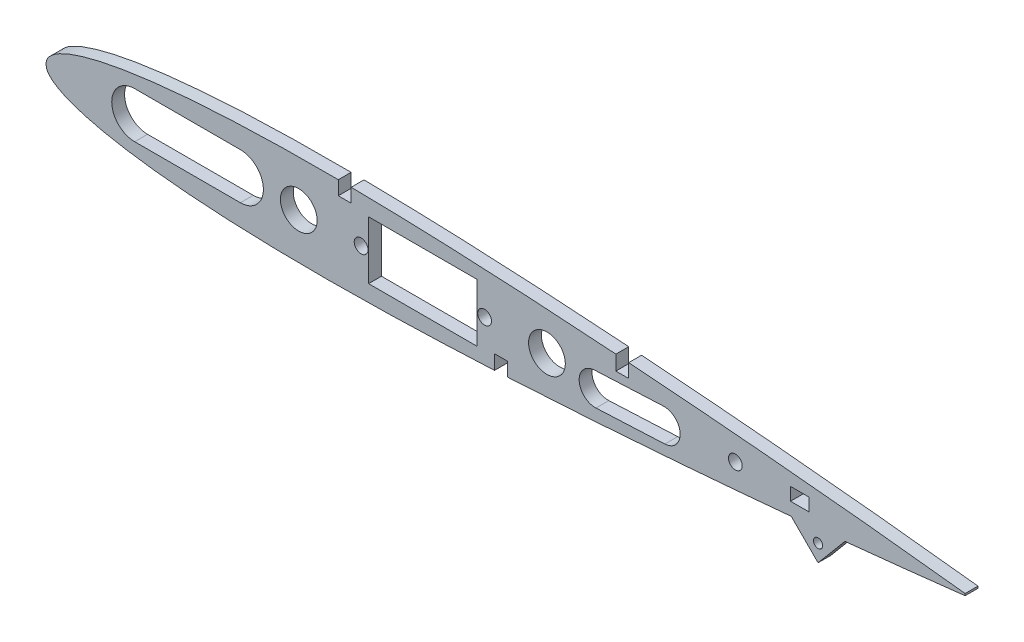
SolidWorks part; units mm, degrees
material "Фанера"
ref_plane "Спереди" through (0, 0, 0) normal (0, 0, 1) x (1, 0, 0)
ref_plane "Сверху" through (0, 0, 0) normal (0, 1, 0) x (1, 0, 0)
ref_plane "Справа" through (0, 0, 0) normal (1, 0, 0) x (0, 0, -1)
curve "Кривая1"
  spline degree 3 poles (200, 0.21, 0) (199.5201, 0.266, 0) (198.1795, 0.4223, 0) (195.7476, 0.7017, 0) (192.5308, 1.0651, 0) (188.7716, 1.4807, 0) (184.587, 1.9325, 0) (180.0562, 2.4092, 0) (175.2384, 2.9026, 0) (170.1814, 3.4057, 0) (164.925, 3.9132, 0) (159.5032, 4.4204, 0) (153.9461, 4.9234, 0) (148.2803, 5.4186, 0) (142.5299, 5.9028, 0) (136.7168, 6.3729, 0) (130.8615, 6.8262, 0) (124.9826, 7.2598, 0) (119.0976, 7.6711, 0) (113.2231, 8.0575, 0) (107.3746, 8.4163, 0) (101.5666, 8.7448, 0) (95.8133, 9.0407, 0) (90.1279, 9.3014, 0) (84.5231, 9.5247, 0) (79.0111, 9.7082, 0) (73.6037, 9.85, 0) (68.3121, 9.9482, 0) (63.1472, 10.0012, 0) (58.1196, 10.0077, 0) (53.2393, 9.9665, 0) (48.5164, 9.8771, 0) (43.9603, 9.7388, 0) (39.5803, 9.5517, 0) (35.3856, 9.3161, 0) (31.3849, 9.0325, 0) (27.5868, 8.7017, 0) (23.9997, 8.3252, 0) (20.6317, 7.9043, 0) (17.4909, 7.4408, 0) (14.5849, 6.9366, 0) (11.9213, 6.3939, 0) (9.5074, 5.8148, 0) (7.3502, 5.2016, 0) (5.4564, 4.5565, 0) (3.8315, 3.8815, 0) (2.4822, 3.178, 0) (1.4075, 2.4454, 0) (0.6238, 1.6789, 0) (0.1006, 0.8638, 0) (0.0324, 0.2785, 0) (0, 0, 0) knots 0 0 0 0 0.007145 0.019956 0.036196 0.055011 0.075879 0.098429 0.122376 0.147488 0.173572 0.20046 0.228005 0.256076 0.284555 0.313333 0.34231 0.371393 0.400496 0.429538 0.458442 0.487136 0.515552 0.543624 0.57129 0.598491 0.62517 0.651272 0.676746 0.701542 0.725611 0.748908 0.771388 0.793008 0.813728 0.833508 0.85231 0.870097 0.886836 0.902493 0.917037 0.930441 0.94268 0.953734 0.96359 0.972247 0.979722 0.986065 0.991385 0.995901 1 1 1 1
curve "Кривая2"
  spline degree 3 poles (0, 0, 0) (0.0324, -0.2785, 0) (0.1006, -0.8638, 0) (0.6238, -1.6789, 0) (1.4075, -2.4454, 0) (2.4822, -3.178, 0) (3.8315, -3.8815, 0) (5.4564, -4.5565, 0) (7.3502, -5.2016, 0) (9.5074, -5.8148, 0) (11.9213, -6.3939, 0) (14.5849, -6.9366, 0) (17.4909, -7.4408, 0) (20.6317, -7.9043, 0) (23.9997, -8.3252, 0) (27.5868, -8.7017, 0) (31.3849, -9.0325, 0) (35.3856, -9.3161, 0) (39.5803, -9.5517, 0) (43.9603, -9.7388, 0) (48.5164, -9.8771, 0) (53.2393, -9.9665, 0) (58.1196, -10.0077, 0) (63.1472, -10.0012, 0) (68.3121, -9.9482, 0) (73.6037, -9.85, 0) (79.0111, -9.7082, 0) (84.5231, -9.5247, 0) (90.1279, -9.3014, 0) (95.8133, -9.0407, 0) (101.5666, -8.7448, 0) (107.3746, -8.4163, 0) (113.2231, -8.0575, 0) (119.0976, -7.6711, 0) (124.9826, -7.2598, 0) (130.8615, -6.8262, 0) (136.7168, -6.3729, 0) (142.5299, -5.9028, 0) (148.2803, -5.4186, 0) (153.9461, -4.9234, 0) (159.5032, -4.4204, 0) (164.925, -3.9132, 0) (170.1814, -3.4057, 0) (175.2384, -2.9026, 0) (180.0562, -2.4092, 0) (184.587, -1.9325, 0) (188.7716, -1.4807, 0) (192.5308, -1.0651, 0) (195.7476, -0.7017, 0) (198.1795, -0.4223, 0) (199.5201, -0.266, 0) (200, -0.21, 0) knots 0 0 0 0 0.004099 0.008615 0.013935 0.020278 0.027753 0.03641 0.046266 0.05732 0.069559 0.082963 0.097507 0.113164 0.129903 0.14769 0.166492 0.186272 0.206992 0.228612 0.251092 0.274389 0.298458 0.323254 0.348728 0.37483 0.401509 0.42871 0.456376 0.484448 0.512864 0.541558 0.570462 0.599504 0.628607 0.65769 0.686667 0.715445 0.743924 0.771995 0.79954 0.826428 0.852512 0.877624 0.901571 0.924121 0.944989 0.963804 0.980044 0.992855 1 1 1 1
sketch "Эскиз3" plane through (0, 0, 0) normal (0, 0, 1) x (1, 0, 0)
  line L0 (200, 0.21) -> (200, -0.21)
  line L1 (63.6, 9.9908) -> (63.6, 6.9656)
  line L2 (63.6, 6.9656) -> (66.4, 6.9656)
  line L3 (66.4, 6.9656) -> (66.4, 9.9656)
  line L4 (97.6, -8.9469) -> (97.6, -5.8023)
  line L5 (97.6, -5.8023) -> (100.4, -5.8023)
  line L6 (100.4, -5.8023) -> (100.4, -8.8023)
  line L7 (124, 7.3263) -> (124, 4.1244)
  line L8 (124, 4.1244) -> (126.8, 4.1244)
  line L9 (126.8, 4.1244) -> (126.8, 7.1244)
  line L10 (19.3, 0) -> (42.3, 0) construction
  line L11 (19.3, 5) -> (42.3, 5)
  line L12 (19.3, -5) -> (42.3, -5)
  line L13 (93.8, 6.3) -> (97.07, 6.3) construction
  line L16 (119.5083, -1.5033) -> (134.4917, -0.7967) construction
  line L17 (119.3435, 1.9928) -> (134.3268, 2.6994)
  line L18 (119.6732, -4.9994) -> (134.6565, -4.2928)
  line L19 (70.2, 6.3) -> (93.8, 6.3)
  line L20 (70.2, 6.3) -> (70.2, -6.3)
  line L21 (70.2, -6.3) -> (93.8, -6.3)
  line L22 (93.8, 6.3) -> (93.8, -6.3)
  line L23 (97.07, 6.3) -> (97.07, -6.3) construction
  line L24 (97.07, -6.3) -> (93.8, -6.3) construction
  line L25 (70.2, 6.3) -> (66.93, 6.3) construction
  line L26 (66.93, 6.3) -> (66.93, -6.3) construction
  line L27 (66.93, -6.3) -> (70.2, -6.3) construction
  line L28 (70.2, 6.3) -> (93.8, -6.3) construction
  line L29 (93.8, 6.3) -> (70.2, -6.3) construction
  line L30 (162.1702, -4.1702) -> (168, -10)
  line L31 (162, 1.4) -> (166, 1.4)
  line L32 (162, 1.4) -> (162, -1.4)
  line L33 (162, -1.4) -> (166, -1.4)
  line L34 (166, 1.4) -> (166, -1.4)
  line L35 (162, 1.4) -> (166, -1.4) construction
  line L36 (162, -1.4) -> (166, 1.4) construction
  line L37 (168, -10) -> (173.8395, -3.0408)
  line L38 (168, 8.0416) -> (168, -13.6699) construction
  circle A0 centre (109, 0) radius 4
  circle A1 centre (55, 0) radius 4
  arc A2 (150, 5.2672) -> (150, -5.2672) centre (150, 0) ccw
  arc A3 (142.8327, 5.8745) -> (142.8327, -5.8745) centre (150, 0) ccw
  circle A4 centre (150, 0) radius 1.5
  arc A5 (19.3, 5) -> (19.3, -5) centre (19.3, 0) ccw
  arc A6 (42.3, -5) -> (42.3, 5) centre (42.3, 0) ccw
  arc A9 (119.3435, 1.9928) -> (119.6732, -4.9994) centre (119.5083, -1.5033) ccw
  arc A10 (134.6565, -4.2928) -> (134.3268, 2.6994) centre (134.4917, -0.7967) ccw
  circle A11 centre (68.565, 0) radius 1.5
  circle A12 centre (95.435, 0) radius 1.5
  circle A13 centre (168, -6.3) radius 1
  spline S0 degree 3 poles (-9532.9695, -2992.5013) (170.2259, 85.6726) (-8.3379, 12.2838) (0.6238, -1.6789) (1.4075, -2.4454) (2.4822, -3.178) (3.8315, -3.8815) (5.4564, -4.5565) (7.3502, -5.2016) (9.5074, -5.8148) (11.9213, -6.3939) (14.5849, -6.9366) (17.4909, -7.4408) (20.6317, -7.9043) (23.9997, -8.3252) (27.5868, -8.7017) (31.3849, -9.0325) (35.3856, -9.3161) (39.5803, -9.5517) (43.9603, -9.7388) (48.5164, -9.8771) (53.2393, -9.9665) (58.1196, -10.0077) (63.1472, -10.0012) (68.3121, -9.9482) (73.6037, -9.85) (79.0111, -9.7082) (84.5231, -9.5247) (90.1279, -9.3014) (95.8133, -9.0407) (101.5666, -8.7448) (107.3746, -8.4163) (113.2231, -8.0575) (119.0976, -7.6711) (124.9826, -7.2598) (130.8615, -6.8262) (136.7168, -6.3729) (142.5299, -5.9028) (148.2803, -5.4186) (153.9461, -4.9234) (161.2601, -4.2614) (168.3719, -3.5857) (175.2384, -2.9026) (180.0562, -2.4092) (184.587, -1.9325) (188.7716, -1.4807) (192.5308, -1.0651) (195.7476, -0.7017) (353.0587, 17.3703) (505.6517, 66.5515) (1814.7464, -9851.1465) knots -0.224768 -0.224768 -0.224768 -0.224768 0.004099 0.008615 0.013935 0.020278 0.027753 0.03641 0.046266 0.05732 0.069559 0.082963 0.097507 0.113164 0.129903 0.14769 0.166492 0.186272 0.206992 0.228612 0.251092 0.274389 0.298458 0.323254 0.348728 0.37483 0.401509 0.42871 0.456376 0.484448 0.512864 0.541558 0.570462 0.599504 0.628607 0.65769 0.686667 0.715445 0.743924 0.771995 0.79954 0.852512 0.877624 0.901571 0.924121 0.944989 0.963804 0.980044 0.992855 3.30514 3.30514 3.30514 3.30514 only from (0, 0) to (200, -0.21) construction
  spline S1 degree 3 poles (1814.7355, 9851.0635) (505.6509, -66.5513) (353.0583, -17.3703) (195.7476, 0.7017) (192.5308, 1.0651) (188.7716, 1.4807) (184.587, 1.9325) (180.0562, 2.4092) (175.2384, 2.9026) (168.3719, 3.5857) (161.2601, 4.2614) (153.9461, 4.9234) (148.2803, 5.4186) (142.5299, 5.9028) (136.7168, 6.3729) (130.8615, 6.8262) (124.9826, 7.2598) (119.0976, 7.6711) (113.2231, 8.0575) (107.3746, 8.4163) (101.5666, 8.7448) (95.8133, 9.0407) (90.1279, 9.3014) (84.5231, 9.5247) (79.0111, 9.7082) (73.6037, 9.85) (68.3121, 9.9482) (63.1472, 10.0012) (58.1196, 10.0077) (53.2393, 9.9665) (48.5164, 9.8771) (43.9603, 9.7388) (39.5803, 9.5517) (35.3856, 9.3161) (31.3849, 9.0325) (27.5868, 8.7017) (23.9997, 8.3252) (20.6317, 7.9043) (17.4909, 7.4408) (14.5849, 6.9366) (11.9213, 6.3939) (9.5074, 5.8148) (7.3502, 5.2016) (5.4564, 4.5565) (3.8315, 3.8815) (2.4822, 3.178) (1.4075, 2.4454) (0.6238, 1.6789) (-8.3377, -12.2835) (170.2179, -85.6693) (-9532.3074, 2992.2912) knots -2.305133 -2.305133 -2.305133 -2.305133 0.007145 0.019956 0.036196 0.055011 0.075879 0.098429 0.122376 0.147488 0.20046 0.228005 0.256076 0.284555 0.313333 0.34231 0.371393 0.400496 0.429538 0.458442 0.487136 0.515552 0.543624 0.57129 0.598491 0.62517 0.651272 0.676746 0.701542 0.725611 0.748908 0.771388 0.793008 0.813728 0.833508 0.85231 0.870097 0.886836 0.902493 0.917037 0.930441 0.94268 0.953734 0.96359 0.972247 0.979722 0.986065 0.991385 0.995901 1.224763 1.224763 1.224763 1.224763 only from (200, 0.21) to (0, 0) construction
  spline S2 degree 3 poles (0, 0) (0.0324, -0.2785) (0.1006, -0.8638) (0.6238, -1.6789) (1.4075, -2.4454) (2.4822, -3.178) (3.8315, -3.8815) (5.4564, -4.5565) (7.3502, -5.2016) (9.5074, -5.8148) (11.9213, -6.3939) (14.5849, -6.9366) (17.4909, -7.4408) (20.6317, -7.9043) (23.9997, -8.3252) (27.5868, -8.7017) (31.3849, -9.0325) (35.3856, -9.3161) (39.5803, -9.5517) (43.9603, -9.7388) (48.5164, -9.8771) (53.2393, -9.9665) (58.1196, -10.0077) (63.1472, -10.0012) (68.3121, -9.9482) (73.6037, -9.85) (79.0111, -9.7082) (84.5231, -9.5247) (90.1279, -9.3014) (94.497, -9.1011) (96.9966, -8.9773) (97.6, -8.9469) knots 0 0 0 0 0.004099 0.008615 0.013935 0.020278 0.027753 0.03641 0.046266 0.05732 0.069559 0.082963 0.097507 0.113164 0.129903 0.14769 0.166492 0.186272 0.206992 0.228612 0.251092 0.274389 0.298458 0.323254 0.348728 0.37483 0.401509 0.42871 0.456376 0.484448 0.493381 0.493381 0.493381 0.493381
  spline S3 degree 3 poles (200, 0.21) (199.5201, 0.266) (198.1795, 0.4223) (195.7476, 0.7017) (192.5308, 1.0651) (188.7716, 1.4807) (184.587, 1.9325) (180.0562, 2.4092) (175.2384, 2.9026) (168.3719, 3.5857) (161.2601, 4.2614) (153.9461, 4.9234) (148.2803, 5.4186) (142.5299, 5.9028) (136.7168, 6.3729) (131.4667, 6.7793) (128.1563, 7.0254) (126.8, 7.1244) knots 0 0 0 0 0.007145 0.019956 0.036196 0.055011 0.075879 0.098429 0.122376 0.147488 0.20046 0.228005 0.256076 0.284555 0.313333 0.34231 0.362417 0.362417 0.362417 0.362417
  spline S4 degree 3 poles (63.6, 9.9908) (63.4338, 9.9918) (61.5906, 10.0032) (58.1196, 10.0077) (53.2393, 9.9665) (48.5164, 9.8771) (43.9603, 9.7388) (39.5803, 9.5517) (35.3856, 9.3161) (31.3849, 9.0325) (27.5868, 8.7017) (23.9997, 8.3252) (20.6317, 7.9043) (17.4909, 7.4408) (14.5849, 6.9366) (11.9213, 6.3939) (9.5074, 5.8148) (7.3502, 5.2016) (5.4564, 4.5565) (3.8315, 3.8815) (2.4822, 3.178) (1.4075, 2.4454) (0.6238, 1.6789) (0.1006, 0.8638) (0.0324, 0.2785) (0, 0) knots 0.674288 0.674288 0.674288 0.674288 0.676746 0.701542 0.725611 0.748908 0.771388 0.793008 0.813728 0.833508 0.85231 0.870097 0.886836 0.902493 0.917037 0.930441 0.94268 0.953734 0.96359 0.972247 0.979722 0.986065 0.991385 0.995901 1 1 1 1
  spline S5 degree 3 poles (100.4, -8.8023) (100.7825, -8.782) (103.1029, -8.6579) (107.3746, -8.4163) (113.2231, -8.0575) (119.0976, -7.6711) (124.9826, -7.2598) (130.8615, -6.8262) (136.7168, -6.3729) (142.5299, -5.9028) (148.2803, -5.4186) (153.9461, -4.9234) (158.5667, -4.5052) (161.296, -4.252) (162.1702, -4.1702) knots 0.5072 0.5072 0.5072 0.5072 0.512864 0.541558 0.570462 0.599504 0.628607 0.65769 0.686667 0.715445 0.743924 0.771995 0.79954 0.812524 0.812524 0.812524 0.812524
  spline S6 degree 3 poles (124, 7.3263) (122.3646, 7.4427) (118.7696, 7.6927) (113.2231, 8.0575) (107.3746, 8.4163) (101.5666, 8.7448) (95.8133, 9.0407) (90.1279, 9.3014) (84.5231, 9.5247) (79.0111, 9.7082) (73.6037, 9.85) (69.4115, 9.9278) (67.0232, 9.9585) (66.4, 9.9656) knots 0.376253 0.376253 0.376253 0.376253 0.400496 0.429538 0.458442 0.487136 0.515552 0.543624 0.57129 0.598491 0.62517 0.651272 0.660487 0.660487 0.660487 0.660487
  spline S7 degree 3 poles (173.8395, -3.0408) (175.9433, -2.8302) (179.564, -2.461) (184.587, -1.9325) (188.7716, -1.4807) (192.5308, -1.0651) (195.7476, -0.7017) (198.1795, -0.4223) (199.5201, -0.266) (200, -0.21) knots 0.870307 0.870307 0.870307 0.870307 0.901571 0.924121 0.944989 0.963804 0.980044 0.992855 1 1 1 1
  point P17 (65, 6.9656)
  point P20 (99, -5.8023)
  point P30 (30.8, 0)
  point P42 (127, -1.15)
  point P50 (82, 0)
  point P55 (68.565, 6.3)
  point P56 (95.435, 6.3)
  point P57 (164, 0)
  dimension "D1" = 8
  dimension "D2" = 8
  dimension "D16" = 5.2672
  dimension "D17" = 9.2672
  dimension "D18" = 3
  dimension "D32" = 3
  dimension "D33" = 3
  dimension "D41" = 2
  dimension "D3" = 109
  dimension "D4" = 55
  dimension "D5" = 2.8
  dimension "D6" = 2.8
  dimension "D7" = 2.8
  dimension "D8" = 10
  dimension "D9" = 10
  dimension "D10" = 15
  dimension "D11" = 3
  dimension "D12" = 3
  dimension "D13" = 3
  dimension "D14" = 150
  dimension "D15" = 10.5344
  dimension "D21" = 23
  dimension "D22" = 10
  dimension "D23" = 19.3
  dimension "D27" = 18
  dimension "D28" = 7
  dimension "D29" = 2.7
  dimension "D26" = 15
  dimension "D30" = 1.15
  dimension "D19" = 12.6
  dimension "D20" = 23.6
  dimension "D24" = 3.27
  dimension "D25" = 3.27
  dimension "D31" = 27
  dimension "D34" = 2.8
  dimension "D35" = 4
  dimension "D36" = 14
  dimension "D37" = 45
  dimension "D38" = 40
  dimension "D39" = 18
  dimension "D40" = 10
  dimension "D42" = 6.3
extrude "Бобышка-Вытянуть3" add sketch "Эскиз3" along normal blind 2.8 contours L7 S6 L3 L2 L1 S4 S2 L4 L5 L6 S5 A3 S3 L9 L8 L19 L22 L21 L20 A0 A1 A6 L12 A5 L11 A10 L18 A9 L17 A11 A12 | A3 S5 A2 S3 | L37 S7 L0 S3 A2 S5 L30 L31 L34 L33 L32 A4 A13
equation "\"D16@Эскиз3\"=\"D15@Эскиз3\"/2"
equation "\"D17@Эскиз3\"=\"D16@Эскиз3\"+4"
